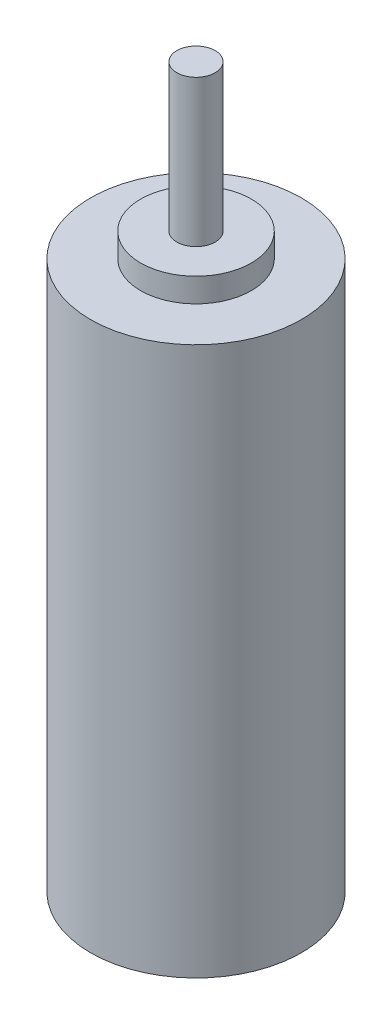
SolidWorks part; units mm, degrees
ref_plane "Front Plane" through (0, 0, 0) normal (0, 0, 1) x (1, 0, 0)
ref_plane "Top Plane" through (0, 0, 0) normal (0, 1, 0) x (1, 0, 0)
ref_plane "Right Plane" through (0, 0, 0) normal (1, 0, 0) x (0, 0, -1)
sketch "Sketch1" plane through (0, 0, 0) normal (0, 1, 0) x (1, 0, 0)
  circle A0 centre (0, 0) radius 11
extrude "Boss-Extrude1" add sketch "Sketch1" along normal blind 57.2
sketch "Sketch2" plane through (0, 57.2, 0) normal (0, 1, 0) x (1, 0, 0)
  circle A0 centre (0, 0) radius 5.7761
extrude "Boss-Extrude2" add sketch "Sketch2" along normal blind 2.5
sketch "Sketch3" plane through (0, 59.7, 0) normal (0, 1, 0) x (1, 0, 0)
  circle A0 centre (0, 0) radius 2
extrude "Boss-Extrude3" add sketch "Sketch3" along normal blind 15.3
